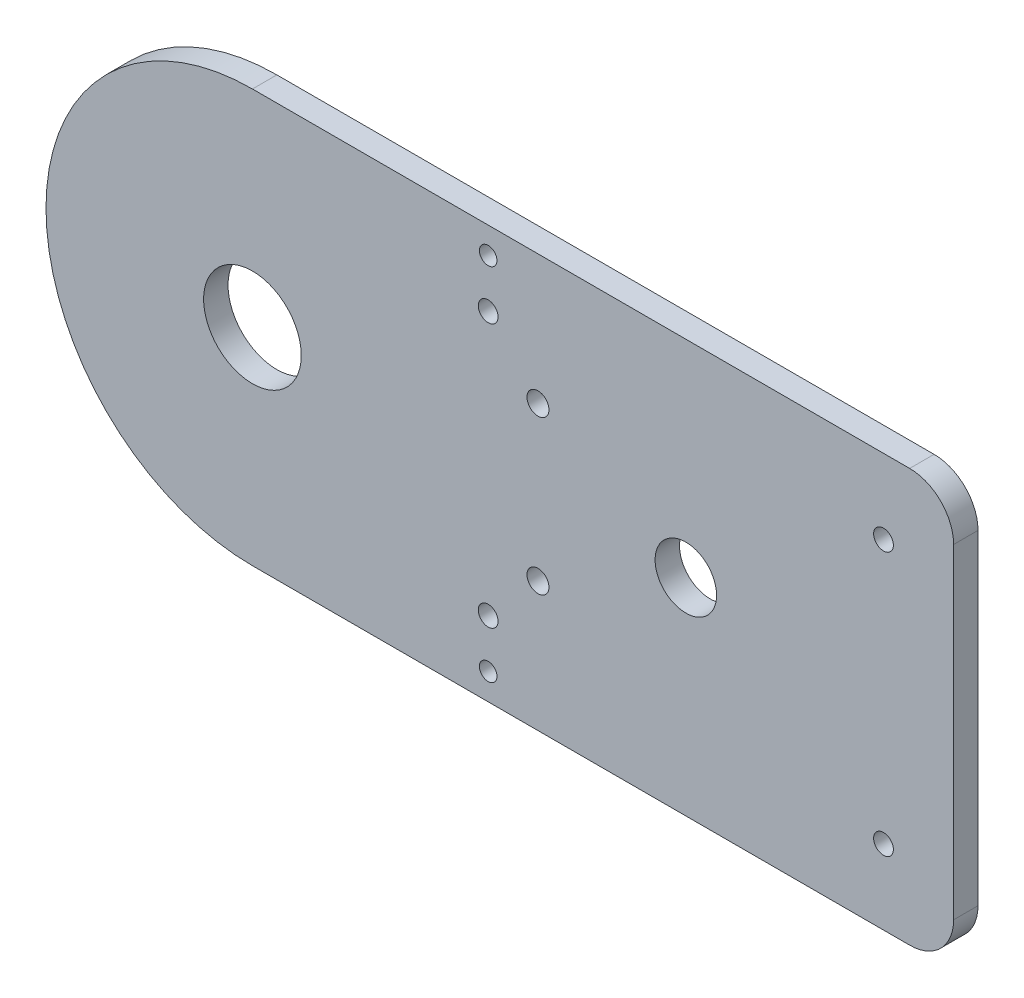
SolidWorks part; units mm, degrees
ref_plane "Front Plane" through (0, 0, 0) normal (0, 0, 1) x (1, 0, 0)
ref_plane "Top Plane" through (0, 0, 0) normal (0, 1, 0) x (1, 0, 0)
ref_plane "Right Plane" through (0, 0, 0) normal (1, 0, 0) x (0, 0, -1)
sketch "Sketch1" plane through (0, 0, 0) normal (0, 0, 1) x (1, 0, 0)
  line L0 (-65, 47) -> (94.6242, 47)
  line L1 (94.6242, 47) -> (94.6242, -47)
  line L2 (94.6242, -47) -> (-65, -47)
  circle A0 centre (-65, 0) radius 11.1125
  arc A1 (-65, 47) -> (-65, -47) centre (-65, 0) ccw
  dimension "D1" = 47
  dimension "D2" = 159.6242
extrude "Boss-Extrude1" add sketch "Sketch1" along normal blind 5.5562
sketch "Sketch2" plane through (0, 0, 5.5562) normal (0, 0, 1) x (1, 0, 0)
  circle A0 centre (33.6664, 0) radius 7
  point P2 (0, 0)
  dimension "D1" = 14
  dimension "D2" = 33.6664
extrude "Cut-Extrude1" cut sketch "Sketch2" against normal blind 5.5562
fillet "Fillet1" radius 10 2 edges at (94.6242, -47, 2.7781) (94.6242, 47, 2.7781)
sketch "Sketch3" plane through (0, 0, 5.5562) normal (0, 0, 1) x (1, 0, 0)
  line L1 (-11.3336, -30) -> (78.6664, -30) construction
  line L2 (-11.3336, -30) -> (-11.3336, 30) construction
  line L3 (-11.3336, 30) -> (78.6664, 30) construction
  line L4 (78.6664, -30) -> (78.6664, 30) construction
  line L5 (-11.3336, -30) -> (78.6664, 30) construction
  line L6 (-11.3336, 30) -> (78.6664, -30) construction
  circle A0 centre (78.6664, 30) radius 2.25
  circle A1 centre (78.6664, -30) radius 2.25
  circle A2 centre (-11.3336, 30) radius 2.25
  circle A3 centre (-11.3336, -30) radius 2.25
  circle A4 centre (-11.3336, 41) radius 2
  circle A5 centre (-11.3336, -41) radius 2
  point P0 (33.6664, 0)
  dimension "D3" = 11
  dimension "D1" = 90
  dimension "D2" = 60
  dimension "D4" = 11
extrude "Cut-Extrude2" cut sketch "Sketch3" against normal blind 6.35
sketch "Sketch4" plane through (0, 0, 5.5562) normal (0, 0, 1) x (1, 0, 0)
  line L0 (0, -17.5) -> (0, 17.5) construction
  circle A1 centre (0, 17.5) radius 2.5
  circle A2 centre (0, -17.5) radius 2.5
  point P4 (0, 0)
  dimension "D1" = 5
extrude "Cut-Extrude3" cut sketch "Sketch4" against normal blind 40
